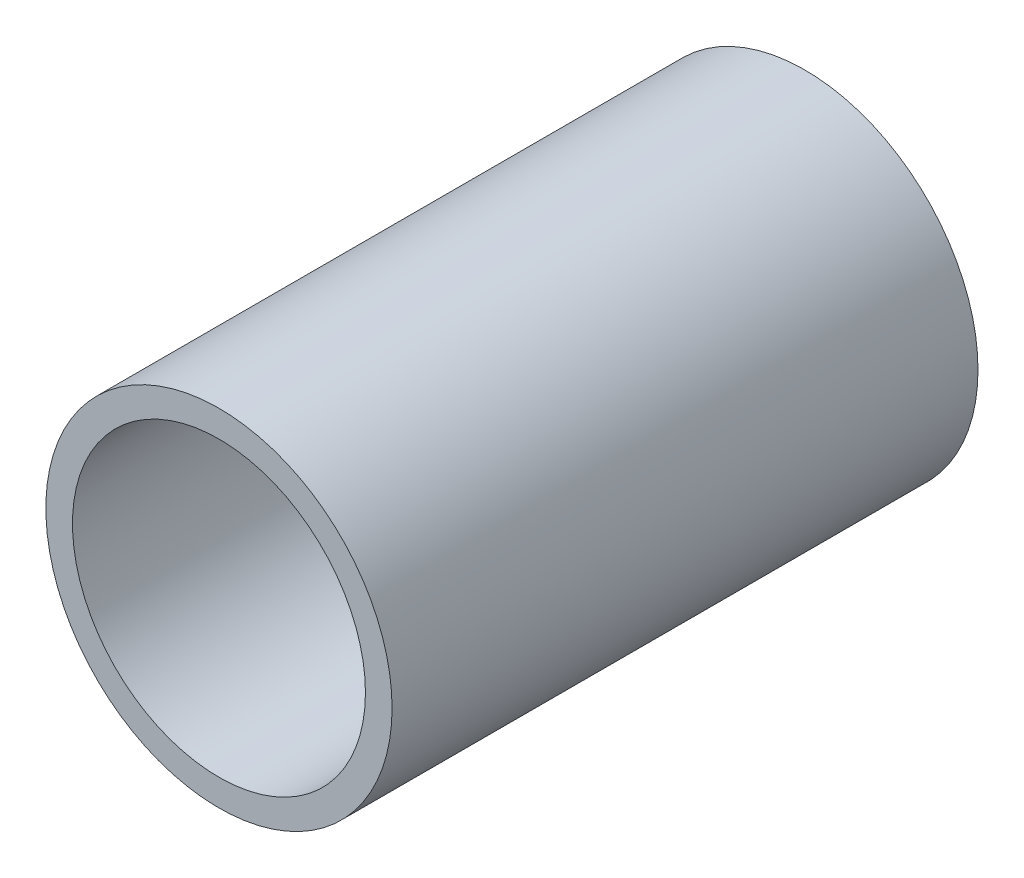
SolidWorks part; units mm, degrees
ref_plane "Front Plane" through (0, 0, 0) normal (0, 0, 1) x (1, 0, 0)
ref_plane "Top Plane" through (0, 0, 0) normal (0, 1, 0) x (1, 0, 0)
ref_plane "Right Plane" through (0, 0, 0) normal (1, 0, 0) x (0, 0, -1)
sketch "Sketch2" plane through (0, 0, 0) normal (0, 0, 1) x (1, 0, 0)
  circle A0 centre (0, 0) radius 3.25
  circle A1 centre (0, 0) radius 2.75
  dimension "D1" = 6.5
  dimension "D2" = 5.5
extrude "Boss-Extrude1" add sketch "Sketch2" along normal blind 11
